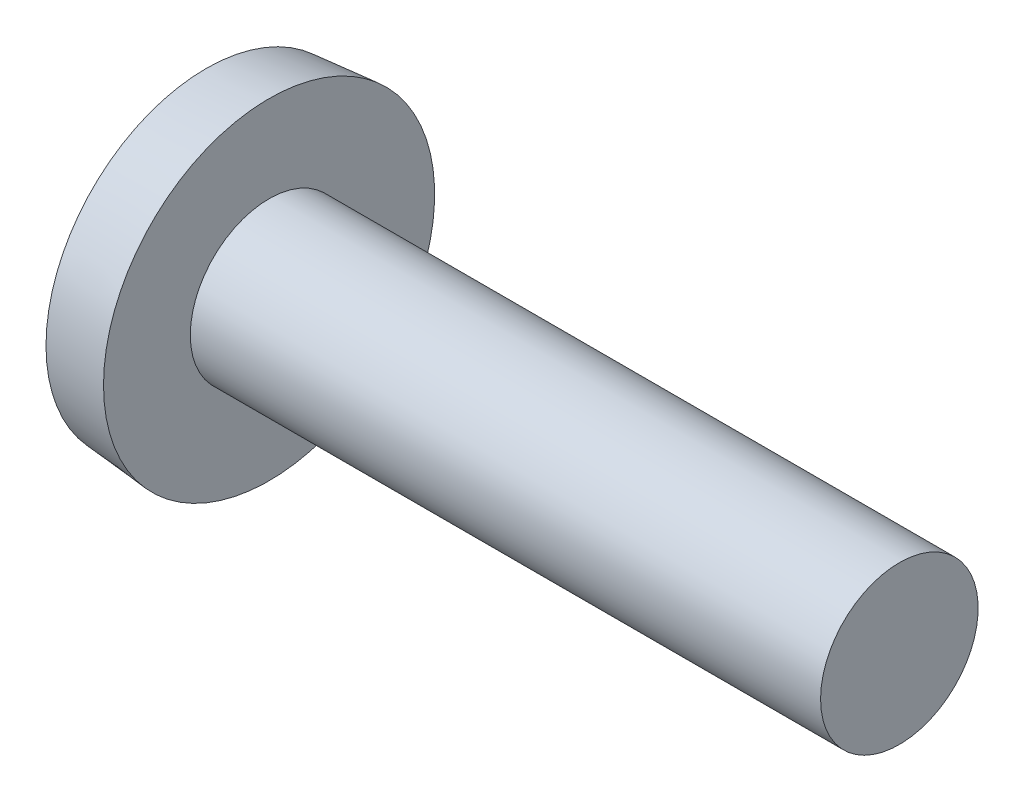
SolidWorks part; units mm, degrees
ref_plane "Plane1" through (0, 0, 0) normal (0, 0, 1) x (1, 0, 0)
ref_plane "Plane2" through (0, 0, 0) normal (0, 1, 0) x (1, 0, 0)
ref_plane "Plane3" through (0, 0, 0) normal (1, 0, 0) x (0, 0, -1)
sketch "BodySke" plane through (0, 0, 0) normal (0, 0, 1) x (1, 0, 0)
  line L0 (6.1976, 4.7625) -> (6.1976, 10.0076)
  line L1 (6.1976, 10.0076) -> (2.3876, 9.6743)
  line L2 (-25.4, 0) -> (127, 0) construction
  line L3 (6.1976, -10.0076) -> (2.3876, -9.6743) construction
  line L4 (6.1976, 4.7625) -> (44.2976, 4.7625)
  line L5 (44.2976, 4.7625) -> (44.2976, 0)
  line L6 (44.2976, 0) -> (0, 0)
  line L7 (6.1976, -4.7625) -> (44.2976, -4.7625) construction
  line L8 (7.2568, 6.35) -> (7.2568, -3.175) construction
  line L9 (37.9476, 6.35) -> (37.9476, -3.175) construction
  arc A0 (0, 0) -> (2.3876, 9.6743) centre (20.7933, 0) cw
  dimension "Head_ang" = 85
  dimension "Oval_ht" = 2.3876
  dimension "Head_ht" = 6.1976
  dimension "Diameter" = 9.525
  dimension "Length" = 38.1
  dimension "Head_dia" = 20.0152
  dimension "Advance" = 1.0592
  dimension "Thread_nom" = 6.35
revolve "Base-Revolve" add sketch "BodySke" angle 360 about L2
cosmetic thread "ThreadCosmetic" [suppressed] parameters "Thread_length"=6.35, "Thread_minor"=4.2266
sketch "Sketch2" plane through (0, 0, 0) normal (1, 0, 0) x (0, 0, -1)
  line L0 (10.0076, -0.8509) -> (10.0076, 0.8509)
  line L1 (10.0076, 0.8509) -> (-10.0076, 0.8509)
  line L2 (-10.0076, 0.8509) -> (-10.0076, -0.8509)
  line L3 (-10.0076, -0.8509) -> (10.0076, -0.8509)
  dimension "D1" = 20.0152
  dimension "D2" = 10.0076
  dimension "D3" = 0.8509
  dimension "Slot_width" = 1.7018
extrude "Slot" cut sketch "Sketch2" along normal blind 2.2606
sketch "Sketch3" plane through (0, 0, 0) normal (1, 0, 0) x (0, 0, -1)
  line L0 (-1.0287, 6.096) -> (1.0287, 6.096)
  line L1 (1.0287, 6.096) -> (1.0287, -6.096)
  line L2 (1.0287, -6.096) -> (-1.0287, -6.096)
  line L3 (-1.0287, -6.096) -> (-1.0287, 6.096)
  dimension "Cross_width" = 2.0574
  dimension "D1" = 1.0287
  dimension "Cross_dia" = 12.192
  dimension "D2" = 6.096
ref_plane "Plane4" through (4.3434, 0, 0) normal (1, 0, 0) x (0, 0, -1)
sketch "Sketch4" plane through (4.3434, 0, 0) normal (1, 0, 0) x (0, 0, -1)
  line L0 (-0.5143, 0.5143) -> (0.5143, 0.5143)
  line L1 (0.5143, 0.5143) -> (0.5144, -0.5143)
  line L2 (0.5144, -0.5143) -> (-0.5143, -0.5144)
  line L3 (-0.5143, -0.5144) -> (-0.5143, 0.5143)
  dimension "D1" = 1.0287
  dimension "D2" = 0.5143
  dimension "D3" = 1.0287
  dimension "D4" = 0.5143
loft "Cross" cut profiles "Sketch3", "Sketch4"
pattern_circular "CirPattern1" count 2 every 90 about axis through (0, 0, 0) along (1, 0, 0) of "Cross"
sketch "ThdSchSke" plane through (0, 0, 0) normal (0, 0, 1) x (1, 0, 0)
  line L0 (37.9476, -2.1133) -> (36.0926, -4.7625)
  line L1 (37.9476, -2.1133) -> (39.8026, -4.7625)
  line L2 (39.8026, -4.7625) -> (39.8026, -5.9531)
  line L3 (-3.175, 0) -> (5.1513, 0) construction
  line L5 (39.8026, -5.9531) -> (36.0926, -5.9531)
  line L6 (36.0926, -5.9531) -> (36.0926, -4.7625)
  dimension "Diameter" = 9.525
  dimension "SideAngle" = 55
  dimension "VeeAngle" = 70
  dimension "Thread_minor" = 4.2266
  dimension "Overcut" = 11.9063
  dimension "Start" = 37.9476
revolve "ThreadSchematic" [suppressed] cut sketch "ThdSchSke" angle 360 about L3
pattern_linear "ThdSchPat" [suppressed]
equation "\"D1@Sketch3\" = \"Cross_width@Sketch3\" / 2"
equation "\"D2@Sketch3\" = \"Cross_dia@Sketch3\" / 2"
equation "\"D1@Sketch4\" = \"Cross_width@Sketch3\"*.5"
equation "\"D2@Sketch4\" = \"D1@Sketch4\" / 2"
equation "\"D3@Sketch4\" = \"D1@Sketch4\""
equation "\"D4@Sketch4\" = \"D2@Sketch4\""
equation "\"D1@Sketch2\" = \"Head_dia@BodySke\""
equation "\"D2@Sketch2\" = \"D1@Sketch2\" / 2"
equation "\"D3@Sketch2\" = \"Slot_width@Sketch2\" / 2"
equation "\"Thread_length@ThreadCosmetic\" = ((sgn( (\"Length@BodySke\" - \"Advance@BodySke\" ) - \"Thread_nom@BodySke\" )-1)*( (\"Length@BodySke\" - \"Advance@BodySke\" ) - \"Thread_nom@BodySke\" ))/-2+ \"Thread_nom@BodySke\""
equation "\"Thread_minor@ThdSchSke\" = \"Thread_minor@ThreadCosmetic\""
equation "\"Diameter@ThdSchSke\" = \"Diameter@BodySke\""
equation "\"Overcut@ThdSchSke\" = \"Diameter@BodySke\" * 1.25"
equation "\"Start@ThdSchSke\" = \"Head_ht@BodySke\" + \"Length@BodySke\" - \"Thread_length@ThreadCosmetic\"  '---Non-countersunk---"
equation "\"Num_threads@ThdSchPat\" = int( \"Thread_length@ThreadCosmetic\" / \"Advance@BodySke\" + 0.999 )  + 1"
equation "\"Advance@ThdSchPat\" = \"Thread_length@ThreadCosmetic\" /  (\"Num_threads@ThdSchPat\" - 1) 'relax it"
